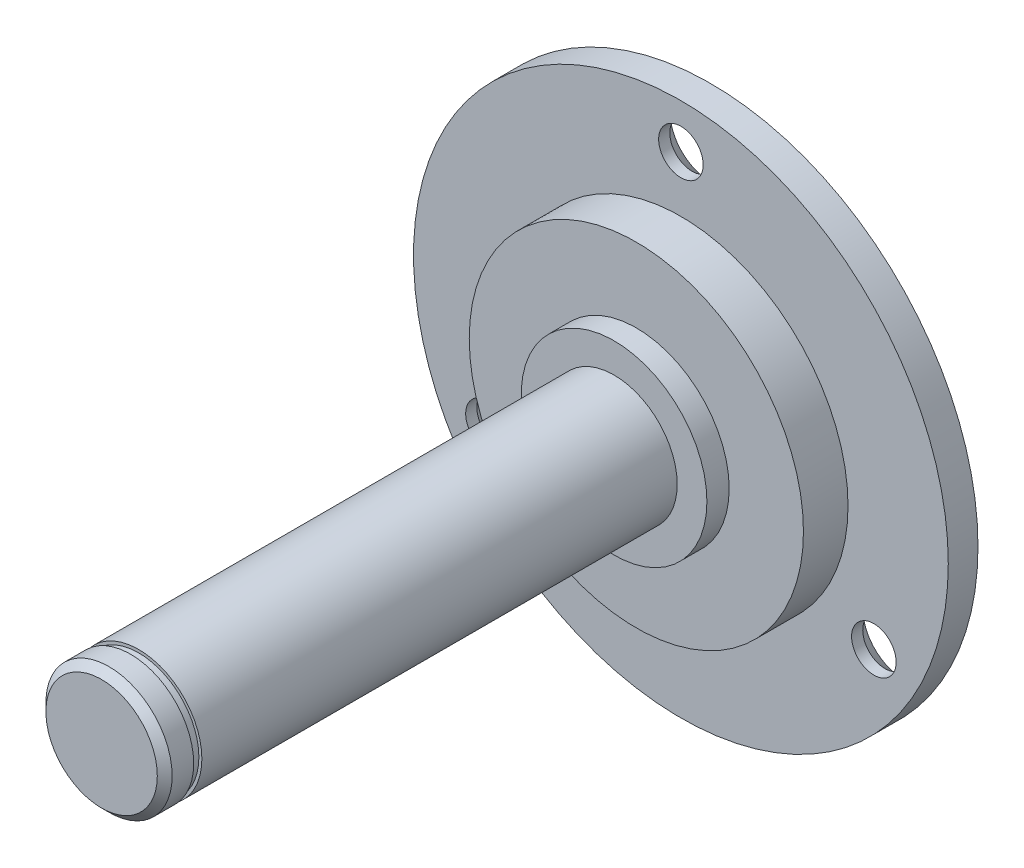
SolidWorks part; units mm, degrees
ref_plane "前视基准面" through (0, 0, 0) normal (0, 0, 1) x (1, 0, 0)
ref_plane "上视基准面" through (0, 0, 0) normal (0, 1, 0) x (1, 0, 0)
ref_plane "右视基准面" through (0, 0, 0) normal (1, 0, 0) x (0, 0, -1)
sketch "草图1" plane through (0, 0, 0) normal (0, 0, 1) x (1, 0, 0)
  circle A0 centre (0, 0) radius 36
  dimension "D1" = 72
extrude "凸台-拉伸1" add sketch "草图1" along normal blind 4
sketch "草图2" plane through (0, 0, 4) normal (0, 0, 1) x (1, 0, 0)
  circle A0 centre (0, 0) radius 22.5
  dimension "D1" = 45
extrude "凸台-拉伸2" add sketch "草图2" along normal blind 6
sketch "草图3" plane through (0, 0, 10) normal (0, 0, 1) x (1, 0, 0)
  circle A0 centre (0, 0) radius 12.5
  dimension "D1" = 25
extrude "凸台-拉伸3" add sketch "草图3" along normal blind 3
sketch "草图4" plane through (0, 0, 13) normal (0, 0, 1) x (1, 0, 0)
  circle A0 centre (0, 0) radius 8.5
  dimension "D1" = 17
extrude "凸台-拉伸4" add sketch "草图4" along normal blind 64
sketch "草图5" plane through (0, 0, 77) normal (0, 0, 1) x (1, 0, 0)
  circle A2 centre (0, 0) radius 8.1
  circle A3 centre (0, 0) radius 8.1
  dimension "D1" = 0.4
extrude "凸台-拉伸5" add sketch "草图5" along normal blind 1.1
sketch "草图6" plane through (0, 0, 78.1) normal (0, 0, 1) x (1, 0, 0)
  circle A0 centre (0, 0) radius 8.5
  dimension "D1" = 17
extrude "凸台-拉伸6" add sketch "草图6" along normal offset from surface (3.9 mm away) 82 up to face at (36, 0, 0)
chamfer "倒角1" distance 1 angle 45 1 edges at (8.5, 0, 82)
sketch "草图7" plane through (0, 0, 0) normal (0, 0, -1) x (-1, 0, 0)
  circle A0 centre (0, 0) radius 30 construction
  point P3 (0, 30)
  point P4 (25.9808, -15)
  point P7 (-25.9808, -15)
  point P8 (-25.9808, -15)
  point P10 (25.9808, -15)
  dimension "D1" = 60
  dimension "D2" = 3
hole_wizard "Ø6.0 (6) 直径孔1" positions "草图7" profile "草图8" hole size "Ø6.0" standard "GB" end condition up to next
sketch "草图8" plane through (-25.9808, -15, 0) normal (1, 0, 0) x (0, 1, 0)
  line L0 (0, 0) -> (0, 4)
  line L1 (0, 4) -> (3, 4)
  line L2 (3, 4) -> (3, 2.5)
  line L3 (3, 2.5) -> (5.5, 0)
  line L5 (5.5, 0) -> (0, 0)
  line L6 (-3, 2.5) -> (-5.5, 0) construction
  line L11 (0, -6.35) -> (0, 107.95) construction
  dimension "通孔孔直径" = 6
  dimension "通孔孔深度" = 4
  dimension "近端锥形沉头孔直径" = 11
  dimension "近端锥形沉头孔角度" = 90
sketch "草图9" plane through (0, 0, 0) normal (1, 0, 0) x (0, 0, -1)
  line L0 (-72.5, 0) -> (-57.5, 0) construction
  line L1 (39.6, 0) -> (-39.6, 0) construction
  line L2 (-72.5, 2.5) -> (-57.5, 2.5)
  line L3 (-72.5, -2.5) -> (-57.5, -2.5)
  line L4 (-13, 12.5) -> (-13, -12.5) construction
  arc A0 (-72.5, 2.5) -> (-72.5, -2.5) centre (-72.5, 0) ccw
  arc A1 (-57.5, -2.5) -> (-57.5, 2.5) centre (-57.5, 0) ccw
  point P5 (-65, 0)
  dimension "D2" = 20
  dimension "D1" = 5
  dimension "D3" = 42
extrude "切除-拉伸1" cut sketch "草图9" against normal through all from offset 5.5
